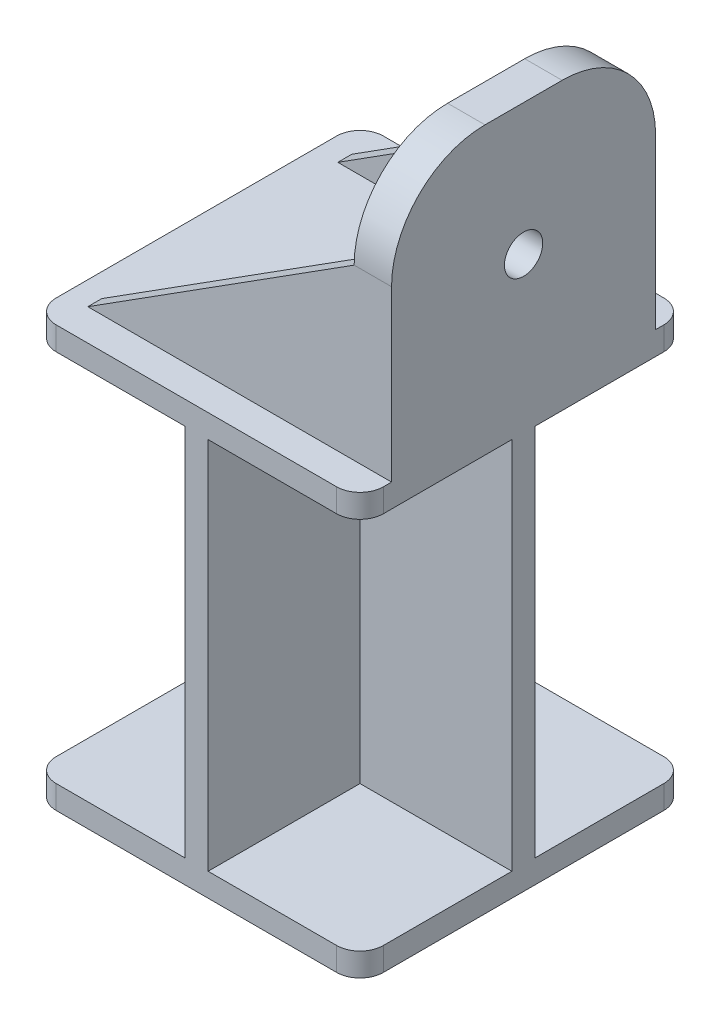
SolidWorks part; units mm, degrees
ref_plane "Front Plane" through (0, 0, 0) normal (0, 0, 1) x (1, 0, 0)
ref_plane "Top Plane" through (0, 0, 0) normal (0, 1, 0) x (1, 0, 0)
ref_plane "Right Plane" through (0, 0, 0) normal (1, 0, 0) x (0, 0, -1)
sketch "Sketch2" plane through (0, 0, 0) normal (0, 1, 0) x (1, 0, 0)
  line L1 (-30, -35) -> (30, -35)
  line L2 (-35, -30) -> (-35, 30)
  line L3 (-30, 35) -> (30, 35)
  line L4 (35, -30) -> (35, 30)
  line L5 (-35, -35) -> (35, 35) construction
  line L6 (-35, 35) -> (35, -35) construction
  arc A0 (30, 35) -> (35, 30) centre (30, 30) cw
  arc A1 (30, -35) -> (35, -30) centre (30, -30) ccw
  arc A2 (-35, -30) -> (-30, -35) centre (-30, -30) ccw
  arc A3 (-30, 35) -> (-35, 30) centre (-30, 30) ccw
  point P0 (0, 0)
  dimension "D3" = 5
  dimension "D1" = 70
  dimension "D2" = 70
extrude "Boss-Extrude1" add sketch "Sketch2" along normal blind 5
sketch "Sketch3" plane through (0, 5, 0) normal (0, 1, 0) x (1, 0, 0)
  line L0 (0, 35) -> (0, -35) construction
  line L1 (30, 35) -> (-30, 35) construction
  line L2 (-30, -35) -> (30, -35) construction
  line L3 (-35, 0) -> (35, 0) construction
  line L4 (-35, 30) -> (-35, -30) construction
  line L5 (35, -30) -> (35, 30) construction
  line L6 (-2.5, 2.5) -> (-2.5, 35)
  line L7 (2.5, -35) -> (-2.5, -35)
  line L8 (2.5, -35) -> (2.5, -2.5)
  line L9 (2.5, 35) -> (-2.5, 35)
  line L10 (-2.5, -35) -> (-2.5, -2.5)
  line L11 (2.5, -35) -> (-2.5, 35) construction
  line L12 (2.5, 35) -> (-2.5, -35) construction
  line L13 (35, -2.5) -> (2.5, -2.5)
  line L14 (35, -2.5) -> (35, 2.5)
  line L15 (35, 2.5) -> (2.5, 2.5)
  line L16 (-35, -2.5) -> (-35, 2.5)
  line L17 (35, -2.5) -> (-35, 2.5) construction
  line L18 (35, 2.5) -> (-35, -2.5) construction
  line L19 (-2.5, 2.5) -> (-35, 2.5)
  line L21 (2.5, 2.5) -> (2.5, 35)
  line L24 (-2.5, -2.5) -> (-35, -2.5)
  point P12 (0, 0)
  point P17 (0, 0)
  dimension "D1" = 5
  dimension "D2" = 5
extrude "Boss-Extrude2" add sketch "Sketch3" along normal blind 80
ref_plane "Plane1" through (0, 45, 0) normal (0, 1, 0) x (1, 0, 0)
mirror "Mirror1" about plane through (0, 45, 0) normal (0, 1, 0) of "Boss-Extrude1"
sketch "Sketch4" plane through (35, 0, 0) normal (1, 0, 0) x (0, 0, -1)
  line L3 (-28.25, 90) -> (28.25, 90)
  line L5 (-28.25, 146.2) -> (28.25, 90) construction
  line L6 (-28.25, 90) -> (28.25, 146.2) construction
  line L7 (0, 133.6259) -> (0, 101.6067) construction
  line L9 (-8.25, 146.2) -> (8.25, 146.2)
  line L10 (-28.25, 90) -> (-28.25, 126.2)
  line L11 (28.25, 126.2) -> (28.25, 90)
  line L12 (-23.8295, 141.9295) -> (0, 118.1) construction
  line L13 (0, 118.1) -> (-25.4302, 118.1) construction
  line L14 (-30, 90) -> (30, 90) construction
  circle A0 centre (0, 118.1) radius 4.1
  arc A7 (8.25, 146.2) -> (28.25, 126.2) centre (8.25, 126.2) cw
  arc A8 (-8.25, 146.2) -> (-28.25, 126.2) centre (-8.25, 126.2) ccw
  point P0 (0, 118.1)
  dimension "D4" = 8.2
  dimension "D2" = 20
  dimension "D1" = 56.2
  dimension "D6" = 45
extrude "Boss-Extrude3" add sketch "Sketch4" against normal blind 8
sketch "Sketch5" plane through (0, 0, 28.25) normal (0, 0, 1) x (1, 0, 0)
  line L3 (35, 90) -> (-30, 90)
  line L7 (-30, 90) -> (27, 126.2)
  line L8 (27, 126.2) -> (35, 126.2)
  line L9 (35, 126.2) -> (35, 90)
extrude "Boss-Extrude4" add sketch "Sketch5" against normal blind 3
ref_plane "Plane2" through (0, 0, 0) normal (0, 0, -1) x (-1, 0, 0)
mirror "Mirror2" about plane through (0, 0, 0) normal (0, 0, -1) of "Boss-Extrude4"
